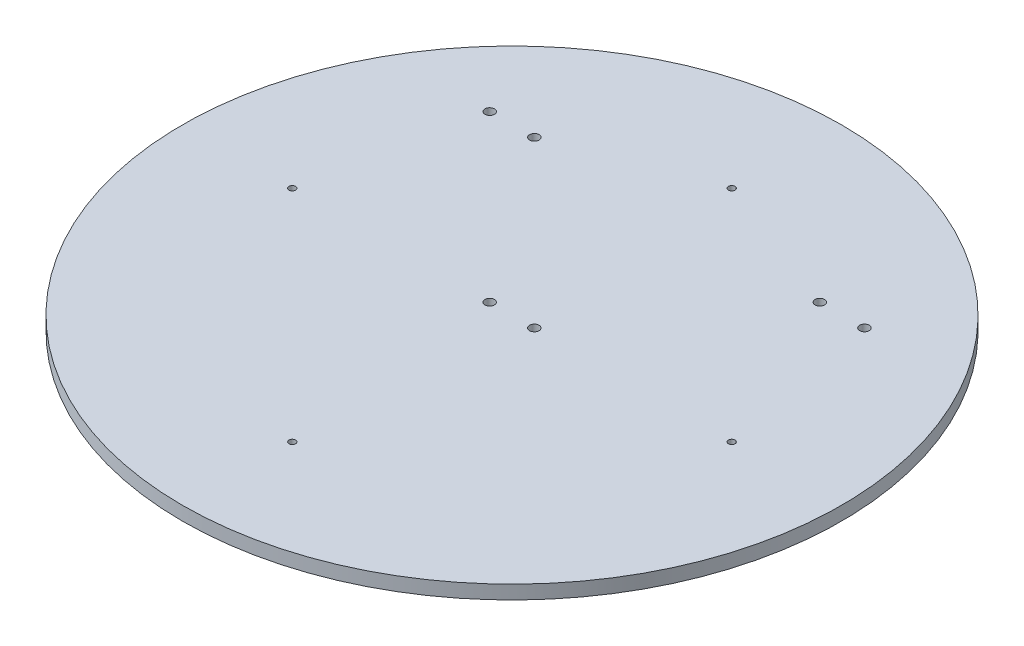
SolidWorks part; units mm, degrees
material "Acrylic (Medium-high impact)"
ref_plane "Front Plane" through (0, 0, 0) normal (0, 0, 1) x (1, 0, 0)
ref_plane "Top Plane" through (0, 0, 0) normal (0, 1, 0) x (1, 0, 0)
ref_plane "Right Plane" through (0, 0, 0) normal (1, 0, 0) x (0, 0, -1)
sketch "Sketch1" plane through (0, 0, 0) normal (0, 1, 0) x (1, 0, 0)
  circle A0 centre (0, 0) radius 152.4
  dimension "D1" = 304.8
extrude "Boss-Extrude1" add sketch "Sketch1" along normal mid plane 6.35
sketch "Sketch3" plane through (0, 3.175, 0) normal (0, 1, 0) x (1, 0, 0)
  line L0 (-10.3187, 0) -> (10.3187, 0) construction
  line L1 (0, 0) -> (76.3322, 76.3322) construction
  line L2 (0, 0) -> (-76.3322, 76.3322) construction
  line L3 (66.0134, 76.3322) -> (86.6509, 76.3322) construction
  line L4 (-86.6509, 76.3322) -> (-66.0134, 76.3322) construction
  circle A0 centre (0, 0) radius 6.477 construction
  circle A1 centre (-10.3187, 0) radius 2.2035
  circle A2 centre (10.3187, 0) radius 2.2034
  circle A3 centre (-10.3187, 0) radius 3.8418 construction
  circle A4 centre (10.3187, 0) radius 3.8418 construction
  circle A5 centre (76.3322, 76.3322) radius 6.477 construction
  circle A6 centre (66.0134, 76.3322) radius 2.2035
  circle A7 centre (86.6509, 76.3322) radius 2.2034
  circle A8 centre (66.0134, 76.3322) radius 3.8418 construction
  circle A9 centre (86.6509, 76.3322) radius 3.8418 construction
  circle A10 centre (-76.3322, 76.3322) radius 6.477 construction
  circle A11 centre (-86.6509, 76.3322) radius 2.2035
  circle A12 centre (-66.0134, 76.3322) radius 2.2034
  circle A13 centre (-86.6509, 76.3322) radius 3.8417 construction
  circle A14 centre (-66.0134, 76.3322) radius 3.8417 construction
  point P6 (0, 0)
  point P18 (76.3322, 76.3322)
  point P29 (-76.3322, 76.3322)
  dimension "D1" = 12.954
  dimension "D2" = 4.4069
  dimension "D3" = 10.3187
  dimension "D4" = 45
  dimension "D5" = 107.95
  dimension "D6" = 10.3187
  dimension "D7" = 10.3187
extrude "Cut-Extrude1" cut sketch "Sketch3" against normal through all
sketch "Sketch5" plane through (0, 3.175, 0) normal (0, 1, 0) x (1, 0, 0)
  line L1 (-71.842, -71.842) -> (71.842, -71.842) construction
  line L2 (-71.842, -71.842) -> (-71.842, 71.842) construction
  line L3 (-71.842, 71.842) -> (71.842, 71.842) construction
  line L4 (71.842, -71.842) -> (71.842, 71.842) construction
  line L5 (-71.842, -71.842) -> (71.842, 71.842) construction
  line L6 (-71.842, 71.842) -> (71.842, -71.842) construction
  circle A0 centre (-71.842, 71.842) radius 1.524 construction
  circle A1 centre (71.842, 71.842) radius 1.524 construction
  circle A2 centre (71.842, -71.842) radius 1.524 construction
  circle A3 centre (-71.842, -71.842) radius 1.524 construction
  circle A4 centre (0, 0) radius 101.6 construction
  circle A5 centre (-101.6, 0) radius 1.524
  circle A6 centre (0, 101.6) radius 1.524
  circle A7 centre (101.6, 0) radius 1.524
  circle A8 centre (0, -101.6) radius 1.524
  dimension "D1" = 3.048
  dimension "D2" = 203.2
extrude "Cut-Extrude3" cut sketch "Sketch5" against normal through all
sketch "Sketch6" [suppressed] plane through (0, 3.9688, 0) normal (0, 1, 0) x (1, 0, 0)
  line L0 (-86.6509, 76.3322) -> (-66.0134, 76.3322) construction
  line L1 (66.0134, 76.3322) -> (86.6509, 76.3322) construction
  circle A0 centre (0, 0) radius 6.477
  circle A1 centre (-76.3322, 76.3322) radius 6.477
  circle A2 centre (76.3322, 76.3322) radius 6.477
  point P11 (-76.3322, 76.3322)
  point P12 (76.3322, 76.3322)
  dimension "D1" = 12.954
extrude "Cut-Extrude4" [suppressed] cut sketch "Sketch6" against normal through all
